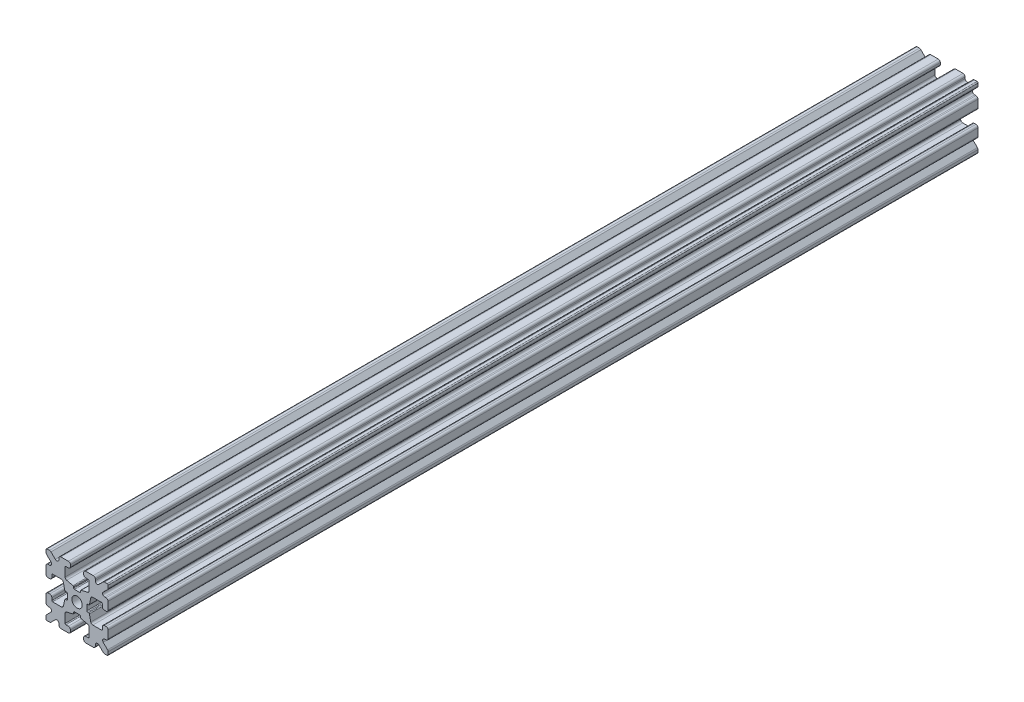
SolidWorks part; units mm, degrees
material "6061-T6 (SS)"
ref_plane "Front Plane" through (0, 0, 0) normal (0, 0, 1) x (1, 0, 0)
ref_plane "Top Plane" through (0, 0, 0) normal (0, 1, 0) x (1, 0, 0)
ref_plane "Right Plane" through (0, 0, 0) normal (1, 0, 0) x (0, 0, -1)
ref_plane "Plane1" through (0, 0, 150) normal (0, 0, 1) x (1, 0, 0)
sketch "Sketch1" plane through (0, 0, 150) normal (0, 0, 1) x (1, 0, 0)
  line L0 (0.9818, -2.97) -> (2.5094, -3.3124)
  line L1 (2.9, -3.8003) -> (2.9, -5.9)
  line L2 (2.7, -6.1) -> (2.1, -6.1)
  line L3 (1.6, -6.6) -> (1.6, -7)
  line L4 (2.1, -7.5) -> (3.9, -7.5)
  line L5 (4.4, -7) -> (4.4, -6.6678)
  line L6 (5.2536, -6.3142) -> (6.2929, -7.3536)
  line L7 (6.6464, -7.5) -> (7.25, -7.5)
  line L8 (7.5, -7.25) -> (7.5, -6.6464)
  line L9 (7.3536, -6.2929) -> (6.3142, -5.2536)
  line L10 (6.6678, -4.4) -> (7, -4.4)
  line L11 (7.5, -3.9) -> (7.5, -2.1)
  line L12 (7, -1.6) -> (6.6, -1.6)
  line L13 (6.1, -2.1) -> (6.1, -2.7)
  line L14 (5.9, -2.9) -> (3.8003, -2.9)
  line L15 (3.3124, -2.5094) -> (2.97, -0.9818)
  line L16 (2.7749, -0.8255) -> (2.5471, -0.8255)
  line L17 (2.3471, -0.6255) -> (2.3471, 0.6255)
  line L18 (2.5471, 0.8255) -> (2.7749, 0.8255)
  line L19 (2.97, 0.9818) -> (3.3124, 2.5094)
  line L20 (3.8003, 2.9) -> (5.9, 2.9)
  line L21 (6.1, 2.7) -> (6.1, 2.1)
  line L22 (6.6, 1.6) -> (7, 1.6)
  line L23 (7.5, 2.1) -> (7.5, 3.9)
  line L24 (7, 4.4) -> (6.6678, 4.4)
  line L25 (6.3142, 5.2536) -> (7.3536, 6.2929)
  line L26 (7.5, 6.6464) -> (7.5, 7.25)
  line L27 (7.25, 7.5) -> (6.6464, 7.5)
  line L28 (6.2929, 7.3536) -> (5.2536, 6.3142)
  line L29 (4.4, 6.6678) -> (4.4, 7)
  line L30 (3.9, 7.5) -> (2.1, 7.5)
  line L31 (1.6, 7) -> (1.6, 6.6)
  line L32 (2.1, 6.1) -> (2.7, 6.1)
  line L33 (2.9, 5.9) -> (2.9, 3.8003)
  line L34 (2.5094, 3.3124) -> (0.9818, 2.97)
  line L35 (0.8255, 2.7749) -> (0.8255, 2.5471)
  line L36 (0.6255, 2.3471) -> (-0.6255, 2.3471)
  line L37 (-0.8255, 2.5471) -> (-0.8255, 2.7749)
  line L38 (-0.9818, 2.97) -> (-2.5094, 3.3124)
  line L39 (-2.9, 3.8003) -> (-2.9, 5.9)
  line L40 (-2.7, 6.1) -> (-2.1, 6.1)
  line L41 (-1.6, 6.6) -> (-1.6, 7)
  line L42 (-2.1, 7.5) -> (-3.9, 7.5)
  line L43 (-4.4, 7) -> (-4.4, 6.6678)
  line L44 (-5.2536, 6.3142) -> (-6.2929, 7.3536)
  line L45 (-6.6464, 7.5) -> (-7.25, 7.5)
  line L46 (-7.5, 7.25) -> (-7.5, 6.6464)
  line L47 (-7.3536, 6.2929) -> (-6.3142, 5.2536)
  line L48 (-6.6678, 4.4) -> (-7, 4.4)
  line L49 (-7.5, 3.9) -> (-7.5, 2.1)
  line L50 (-7, 1.6) -> (-6.6, 1.6)
  line L51 (-6.1, 2.1) -> (-6.1, 2.7)
  line L52 (-5.9, 2.9) -> (-3.8003, 2.9)
  line L53 (-3.3124, 2.5094) -> (-2.97, 0.9818)
  line L54 (-2.7749, 0.8255) -> (-2.5471, 0.8255)
  line L55 (-2.3471, 0.6255) -> (-2.3471, -0.6255)
  line L56 (-2.5471, -0.8255) -> (-2.7749, -0.8255)
  line L57 (-2.97, -0.9818) -> (-3.3124, -2.5094)
  line L58 (-3.8003, -2.9) -> (-5.9, -2.9)
  line L59 (-6.1, -2.7) -> (-6.1, -2.1)
  line L60 (-6.6, -1.6) -> (-7, -1.6)
  line L61 (-7.5, -2.1) -> (-7.5, -3.9)
  line L62 (-7, -4.4) -> (-6.6678, -4.4)
  line L63 (-6.3142, -5.2536) -> (-7.3536, -6.2929)
  line L64 (-7.5, -6.6464) -> (-7.5, -7.25)
  line L65 (-7.25, -7.5) -> (-6.6464, -7.5)
  line L66 (-6.2929, -7.3536) -> (-5.2536, -6.3142)
  line L67 (-4.4, -6.6678) -> (-4.4, -7)
  line L68 (-3.9, -7.5) -> (-2.1, -7.5)
  line L69 (-1.6, -7) -> (-1.6, -6.6)
  line L70 (-2.1, -6.1) -> (-2.7, -6.1)
  line L71 (-2.9, -5.9) -> (-2.9, -3.8003)
  line L72 (-2.5094, -3.3124) -> (-0.9818, -2.97)
  line L73 (-0.8255, -2.7749) -> (-0.8255, -2.5471)
  line L74 (-0.6255, -2.3471) -> (0.6255, -2.3471)
  line L75 (0.8255, -2.5471) -> (0.8255, -2.7749)
  circle A0 centre (0, 0) radius 1.25
  arc A1 (0.8255, -2.7749) -> (0.9818, -2.97) centre (1.0255, -2.7749) ccw
  arc A2 (2.5094, -3.3124) -> (2.9, -3.8003) centre (2.4, -3.8003) cw
  arc A3 (2.9, -5.9) -> (2.7, -6.1) centre (2.7, -5.9) cw
  arc A4 (2.1, -6.1) -> (1.6, -6.6) centre (2.1, -6.6) ccw
  arc A5 (1.6, -7) -> (2.1, -7.5) centre (2.1, -7) ccw
  arc A6 (3.9, -7.5) -> (4.4, -7) centre (3.9, -7) ccw
  arc A7 (4.4, -6.6678) -> (5.2536, -6.3142) centre (4.9, -6.6678) cw
  arc A8 (6.2929, -7.3536) -> (6.6464, -7.5) centre (6.6464, -7) ccw
  arc A9 (7.25, -7.5) -> (7.5, -7.25) centre (7.25, -7.25) ccw
  arc A10 (7.5, -6.6464) -> (7.3536, -6.2929) centre (7, -6.6464) ccw
  arc A11 (6.3142, -5.2536) -> (6.6678, -4.4) centre (6.6678, -4.9) cw
  arc A12 (7, -4.4) -> (7.5, -3.9) centre (7, -3.9) ccw
  arc A13 (7.5, -2.1) -> (7, -1.6) centre (7, -2.1) ccw
  arc A14 (6.6, -1.6) -> (6.1, -2.1) centre (6.6, -2.1) ccw
  arc A15 (6.1, -2.7) -> (5.9, -2.9) centre (5.9, -2.7) cw
  arc A16 (3.8003, -2.9) -> (3.3124, -2.5094) centre (3.8003, -2.4) cw
  arc A17 (2.97, -0.9818) -> (2.7749, -0.8255) centre (2.7749, -1.0255) ccw
  arc A18 (2.5471, -0.8255) -> (2.3471, -0.6255) centre (2.5471, -0.6255) cw
  arc A19 (2.3471, 0.6255) -> (2.5471, 0.8255) centre (2.5471, 0.6255) cw
  arc A20 (2.7749, 0.8255) -> (2.97, 0.9818) centre (2.7749, 1.0255) ccw
  arc A21 (3.3124, 2.5094) -> (3.8003, 2.9) centre (3.8003, 2.4) cw
  arc A22 (5.9, 2.9) -> (6.1, 2.7) centre (5.9, 2.7) cw
  arc A23 (6.1, 2.1) -> (6.6, 1.6) centre (6.6, 2.1) ccw
  arc A24 (7, 1.6) -> (7.5, 2.1) centre (7, 2.1) ccw
  arc A25 (7.5, 3.9) -> (7, 4.4) centre (7, 3.9) ccw
  arc A26 (6.6678, 4.4) -> (6.3142, 5.2536) centre (6.6678, 4.9) cw
  arc A27 (7.3536, 6.2929) -> (7.5, 6.6464) centre (7, 6.6464) ccw
  arc A28 (7.5, 7.25) -> (7.25, 7.5) centre (7.25, 7.25) ccw
  arc A29 (6.6464, 7.5) -> (6.2929, 7.3536) centre (6.6464, 7) ccw
  arc A30 (5.2536, 6.3142) -> (4.4, 6.6678) centre (4.9, 6.6678) cw
  arc A31 (4.4, 7) -> (3.9, 7.5) centre (3.9, 7) ccw
  arc A32 (2.1, 7.5) -> (1.6, 7) centre (2.1, 7) ccw
  arc A33 (1.6, 6.6) -> (2.1, 6.1) centre (2.1, 6.6) ccw
  arc A34 (2.7, 6.1) -> (2.9, 5.9) centre (2.7, 5.9) cw
  arc A35 (2.9, 3.8003) -> (2.5094, 3.3124) centre (2.4, 3.8003) cw
  arc A36 (0.9818, 2.97) -> (0.8255, 2.7749) centre (1.0255, 2.7749) ccw
  arc A37 (0.8255, 2.5471) -> (0.6255, 2.3471) centre (0.6255, 2.5471) cw
  arc A38 (-0.6255, 2.3471) -> (-0.8255, 2.5471) centre (-0.6255, 2.5471) cw
  arc A39 (-0.8255, 2.7749) -> (-0.9818, 2.97) centre (-1.0255, 2.7749) ccw
  arc A40 (-2.5094, 3.3124) -> (-2.9, 3.8003) centre (-2.4, 3.8003) cw
  arc A41 (-2.9, 5.9) -> (-2.7, 6.1) centre (-2.7, 5.9) cw
  arc A42 (-2.1, 6.1) -> (-1.6, 6.6) centre (-2.1, 6.6) ccw
  arc A43 (-1.6, 7) -> (-2.1, 7.5) centre (-2.1, 7) ccw
  arc A44 (-3.9, 7.5) -> (-4.4, 7) centre (-3.9, 7) ccw
  arc A45 (-4.4, 6.6678) -> (-5.2536, 6.3142) centre (-4.9, 6.6678) cw
  arc A46 (-6.2929, 7.3536) -> (-6.6464, 7.5) centre (-6.6464, 7) ccw
  arc A47 (-7.25, 7.5) -> (-7.5, 7.25) centre (-7.25, 7.25) ccw
  arc A48 (-7.5, 6.6464) -> (-7.3536, 6.2929) centre (-7, 6.6464) ccw
  arc A49 (-6.3142, 5.2536) -> (-6.6678, 4.4) centre (-6.6678, 4.9) cw
  arc A50 (-7, 4.4) -> (-7.5, 3.9) centre (-7, 3.9) ccw
  arc A51 (-7.5, 2.1) -> (-7, 1.6) centre (-7, 2.1) ccw
  arc A52 (-6.6, 1.6) -> (-6.1, 2.1) centre (-6.6, 2.1) ccw
  arc A53 (-6.1, 2.7) -> (-5.9, 2.9) centre (-5.9, 2.7) cw
  arc A54 (-3.8003, 2.9) -> (-3.3124, 2.5094) centre (-3.8003, 2.4) cw
  arc A55 (-2.97, 0.9818) -> (-2.7749, 0.8255) centre (-2.7749, 1.0255) ccw
  arc A56 (-2.5471, 0.8255) -> (-2.3471, 0.6255) centre (-2.5471, 0.6255) cw
  arc A57 (-2.3471, -0.6255) -> (-2.5471, -0.8255) centre (-2.5471, -0.6255) cw
  arc A58 (-2.7749, -0.8255) -> (-2.97, -0.9818) centre (-2.7749, -1.0255) ccw
  arc A59 (-3.3124, -2.5094) -> (-3.8003, -2.9) centre (-3.8003, -2.4) cw
  arc A60 (-5.9, -2.9) -> (-6.1, -2.7) centre (-5.9, -2.7) cw
  arc A61 (-6.1, -2.1) -> (-6.6, -1.6) centre (-6.6, -2.1) ccw
  arc A62 (-7, -1.6) -> (-7.5, -2.1) centre (-7, -2.1) ccw
  arc A63 (-7.5, -3.9) -> (-7, -4.4) centre (-7, -3.9) ccw
  arc A64 (-6.6678, -4.4) -> (-6.3142, -5.2536) centre (-6.6678, -4.9) cw
  arc A65 (-7.3536, -6.2929) -> (-7.5, -6.6464) centre (-7, -6.6464) ccw
  arc A66 (-7.5, -7.25) -> (-7.25, -7.5) centre (-7.25, -7.25) ccw
  arc A67 (-6.6464, -7.5) -> (-6.2929, -7.3536) centre (-6.6464, -7) ccw
  arc A68 (-5.2536, -6.3142) -> (-4.4, -6.6678) centre (-4.9, -6.6678) cw
  arc A69 (-4.4, -7) -> (-3.9, -7.5) centre (-3.9, -7) ccw
  arc A70 (-2.1, -7.5) -> (-1.6, -7) centre (-2.1, -7) ccw
  arc A71 (-1.6, -6.6) -> (-2.1, -6.1) centre (-2.1, -6.6) ccw
  arc A72 (-2.7, -6.1) -> (-2.9, -5.9) centre (-2.7, -5.9) cw
  arc A73 (-2.9, -3.8003) -> (-2.5094, -3.3124) centre (-2.4, -3.8003) cw
  arc A74 (-0.9818, -2.97) -> (-0.8255, -2.7749) centre (-1.0255, -2.7749) ccw
  arc A75 (-0.8255, -2.5471) -> (-0.6255, -2.3471) centre (-0.6255, -2.5471) cw
  arc A76 (0.6255, -2.3471) -> (0.8255, -2.5471) centre (0.6255, -2.5471) cw
extrude "Boss-Extrude1" add sketch "Sketch1" against normal blind 210
